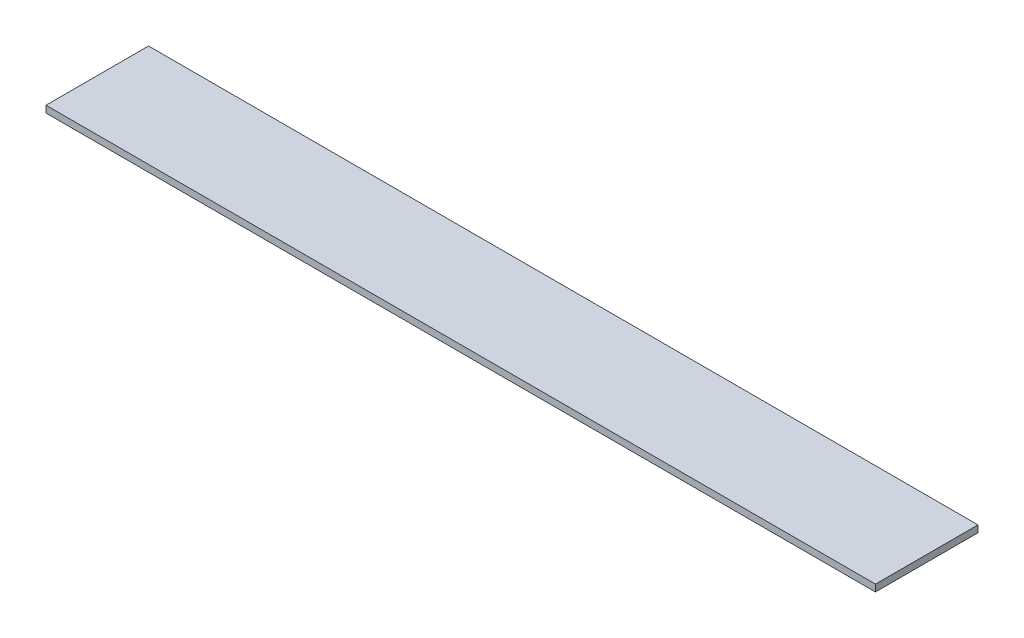
SolidWorks part; units mm, degrees
ref_plane "Front Plane" through (0, 0, 0) normal (0, 0, 1) x (1, 0, 0)
ref_plane "Top Plane" through (0, 0, 0) normal (0, 1, 0) x (1, 0, 0)
ref_plane "Right Plane" through (0, 0, 0) normal (1, 0, 0) x (0, 0, -1)
sketch "Sketch1" plane through (0, 0, 0) normal (0, 0, 1) x (1, 0, 0)
  line L1 (91, 0.75) -> (-91, 0.75)
  line L2 (91, 0.75) -> (91, -0.75)
  line L3 (91, -0.75) -> (-91, -0.75)
  line L4 (-91, 0.75) -> (-91, -0.75)
  line L5 (0, -0.75) -> (0, 0.75) construction
  line L6 (91, 0) -> (-91, 0) construction
  point P0 (0, 0)
  dimension "D1" = 182
  dimension "D2" = 1.5
extrude "Boss-Extrude1" add sketch "Sketch1" along normal blind 22.5
